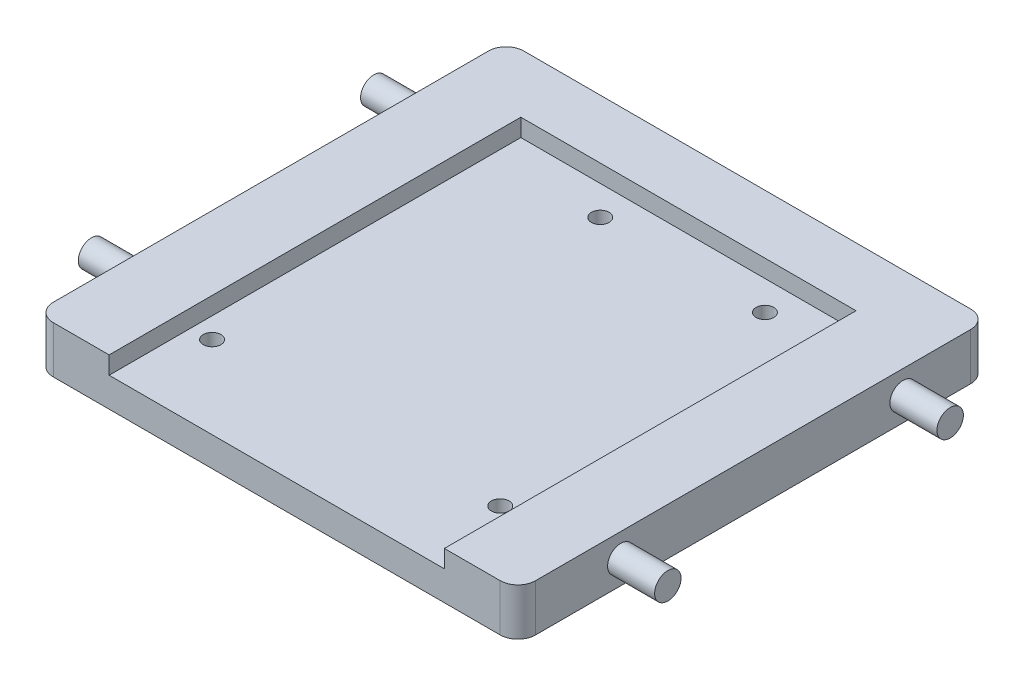
SolidWorks part; units mm, degrees
ref_plane "Front Plane" through (0, 0, 0) normal (0, 0, 1) x (1, 0, 0)
ref_plane "Top Plane" through (0, 0, 0) normal (0, 1, 0) x (1, 0, 0)
ref_plane "Right Plane" through (0, 0, 0) normal (1, 0, 0) x (0, 0, -1)
sketch "Sketch1" plane through (0, 0, 0) normal (0, 1, 0) x (1, 0, 0)
  line L0 (-41, 0) -> (41, 0)
  line L1 (41, 0) -> (41, 80)
  line L2 (41, 80) -> (-41, 80)
  line L3 (-41, 80) -> (-41, 0)
  point P5 (0, 80)
  dimension "D1" = 82
  dimension "D2" = 80
extrude "Boss-Extrude1" add sketch "Sketch1" along normal blind 8
sketch "Sketch2" plane through (41, 0, 0) normal (1, 0, 0) x (0, 0, -1)
  line L0 (0, 4) -> (80, 4) construction
  line L1 (0, 8) -> (0, 0) construction
  line L2 (80, 8) -> (80, 0) construction
  line L3 (40, 8) -> (40, 0) construction
  line L4 (0, 8) -> (80, 8) construction
  line L5 (0, 0) -> (80, 0) construction
  circle A0 centre (17.5, 4) radius 2.25
  circle A1 centre (65.5, 4) radius 2.25
  dimension "D2" = 4.5
  dimension "D3" = 4.5
  dimension "D1" = 48
  dimension "D4" = 22.5
extrude "Boss-Extrude2" add sketch "Sketch2" along normal blind 8 and the other way offset from surface (90 mm away) 8 other way up to face at (-41, 4, -40)
sketch "Sketch3" plane through (0, 8, 0) normal (0, 1, 0) x (1, 0, 0)
  line L0 (0, 70) -> (0, 0) construction
  line L1 (28.5, 0) -> (-28.5, 0)
  line L2 (28.5, 0) -> (28.5, 70)
  line L3 (28.5, 70) -> (-28.5, 70)
  line L4 (-28.5, 0) -> (-28.5, 70)
  line L11 (-41, 0) -> (41, 0) construction
  dimension "D1" = 57
  dimension "D2" = 70
extrude "Cut-Extrude1" cut sketch "Sketch3" against normal blind 3
sketch "Sketch4" plane through (0, 5, 0) normal (0, 1, 0) x (1, 0, 0)
  line L1 (28.5, 0) -> (28.5, 70) construction
  line L3 (-28.5, 0) -> (28.5, 0) construction
  circle A0 centre (-25, 14) radius 1.5
  circle A1 centre (-10, 65) radius 1.5
  circle A2 centre (18, 65) radius 1.5
  circle A3 centre (24, 14) radius 1.5
  circle A4 centre (-25, 14) radius 3
  circle A5 centre (-10, 65) radius 3
  circle A6 centre (18, 65) radius 3
  circle A7 centre (24, 14) radius 3
  dimension "D5" = 3
  dimension "D6" = 3
  dimension "D7" = 3
  dimension "D8" = 3
  dimension "D11" = 6
  dimension "D12" = 6
  dimension "D13" = 6
  dimension "D14" = 6
  dimension "D1" = 51
  dimension "D2" = 28
  dimension "D3" = 6
  dimension "D4" = 15
  dimension "D9" = 14
  dimension "D10" = 10.5
extrude "Cut-Extrude2" cut sketch "Sketch4" against normal blind 3 contours A0 | A1 | A2 | A3
fillet "Fillet1" radius 3 4 edges at (-41, 4, -80) (41, 4, -80) (41, 4, 0) (-41, 4, 0)
